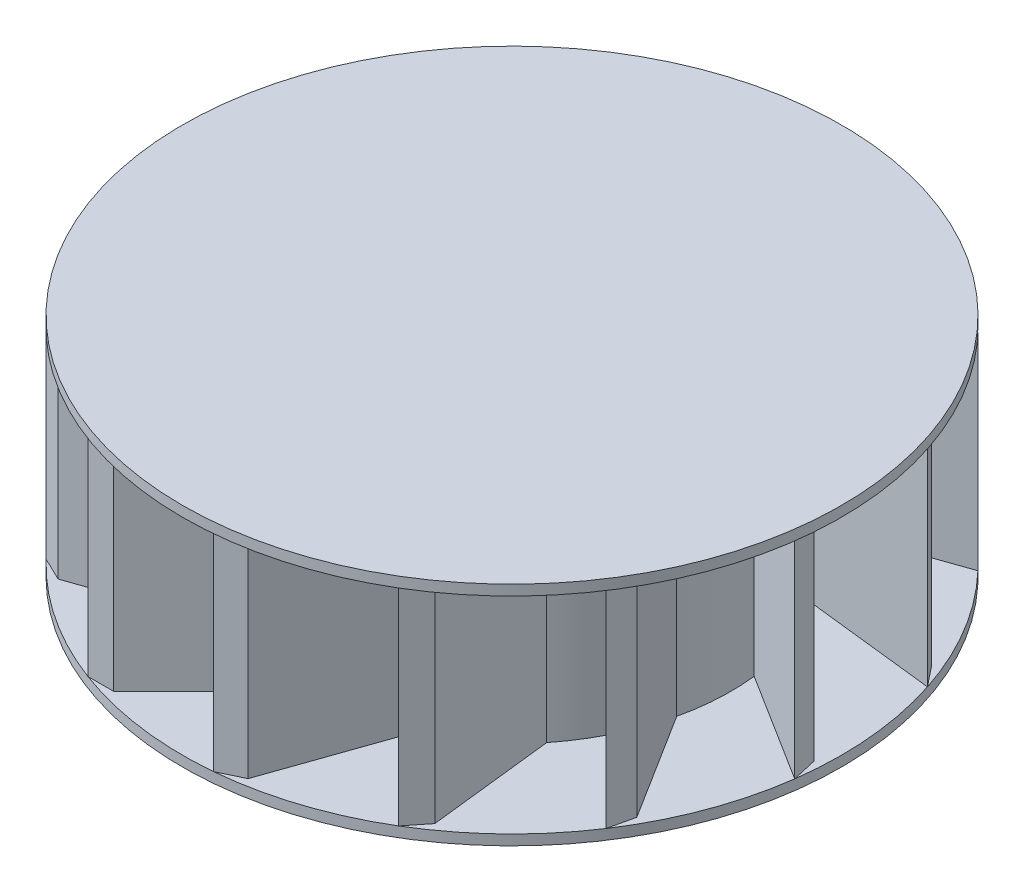
SolidWorks part; units mm, degrees
ref_plane "Front Plane" through (0, 0, 0) normal (0, 0, 1) x (1, 0, 0)
ref_plane "Top Plane" through (0, 0, 0) normal (0, 1, 0) x (1, 0, 0)
ref_plane "Right Plane" through (0, 0, 0) normal (1, 0, 0) x (0, 0, -1)
sketch "Sketch1" plane through (0, 0, 0) normal (0, 1, 0) x (1, 0, 0)
  circle A0 centre (0, 0) radius 42.5
  circle A1 centre (0, 0) radius 3.75
  dimension "D4" = 7.5
  dimension "6.5" = 85
extrude "Boss-Extrude1" add sketch "Sketch1" along normal blind 40
sketch "Sketch2" plane through (0, 0, 0) normal (0, -1, 0) x (1, 0, 0)
  line L0 (0, -42.5) -> (17.413, -59.913)
  line L1 (17.413, -59.913) -> (22.413, -59.913)
  line L2 (22.413, -59.913) -> (4.7354, -42.2354)
  line L4 (0, -42.5) -> (17.0282, -42.5) construction
  line L5 (-18.4401, -38.2912) -> (-10.3067, -61.535)
  line L6 (-5.8018, -63.7044) -> (-14.0588, -40.1074)
  line L7 (-10.3067, -61.535) -> (-5.8018, -63.7044)
  line L8 (-33.2278, -26.4983) -> (-35.985, -50.9692)
  line L9 (-32.8676, -54.8784) -> (-30.0685, -30.0356)
  line L10 (-35.985, -50.9692) -> (-32.8676, -54.8784)
  line L11 (-41.4344, -9.4571) -> (-54.5361, -30.3084)
  line L12 (-53.4235, -35.183) -> (-40.1227, -14.0149)
  line L13 (-54.5361, -30.3084) -> (-53.4235, -35.183)
  line L14 (-41.4344, 9.4571) -> (-62.2857, -3.6446)
  line L15 (-63.3983, -8.5192) -> (-42.2302, 4.7816)
  line L16 (-62.2857, -3.6446) -> (-63.3983, -8.5192)
  line L17 (-33.2278, 26.4983) -> (-57.6987, 23.7411)
  line L18 (-60.8162, 19.8319) -> (-35.9734, 22.6311)
  line L19 (-57.6987, 23.7411) -> (-60.8162, 19.8319)
  line L20 (-18.4401, 38.2912) -> (-41.6839, 46.4245)
  line L21 (-46.1887, 44.2551) -> (-22.5917, 35.9982)
  line L22 (-41.6839, 46.4245) -> (-46.1887, 44.2551)
  line L23 (0, 42.5) -> (-17.413, 59.913)
  line L24 (-22.413, 59.913) -> (-4.7354, 42.2354)
  line L25 (-17.413, 59.913) -> (-22.413, 59.913)
  line L26 (18.4401, 38.2912) -> (10.3067, 61.535)
  line L27 (5.8018, 63.7044) -> (14.0588, 40.1074)
  line L28 (10.3067, 61.535) -> (5.8018, 63.7044)
  line L29 (33.2278, 26.4983) -> (35.985, 50.9692)
  line L30 (32.8676, 54.8784) -> (30.0685, 30.0356)
  line L31 (35.985, 50.9692) -> (32.8676, 54.8784)
  line L32 (41.4344, 9.4571) -> (54.5361, 30.3084)
  line L33 (53.4235, 35.183) -> (40.1227, 14.0149)
  line L34 (54.5361, 30.3084) -> (53.4235, 35.183)
  line L35 (41.4344, -9.4571) -> (62.2857, 3.6446)
  line L36 (63.3983, 8.5192) -> (42.2302, -4.7816)
  line L37 (62.2857, 3.6446) -> (63.3983, 8.5192)
  line L38 (33.2278, -26.4983) -> (57.6987, -23.7411)
  line L39 (60.8162, -19.8319) -> (35.9734, -22.6311)
  line L40 (57.6987, -23.7411) -> (60.8162, -19.8319)
  line L41 (18.4401, -38.2912) -> (41.6839, -46.4245)
  line L42 (46.1887, -44.2551) -> (22.5917, -35.9982)
  line L43 (41.6839, -46.4245) -> (46.1887, -44.2551)
  circle A0 centre (0, 0) radius 42.5 construction
  arc A1 (0, -42.5) -> (4.7354, -42.2354) centre (0, 0) ccw
  arc A2 (-18.4401, -38.2912) -> (-14.0588, -40.1074) centre (0, 0) ccw
  arc A3 (-33.2278, -26.4983) -> (-30.0685, -30.0356) centre (0, 0) ccw
  arc A4 (-41.4344, -9.4571) -> (-40.1227, -14.0149) centre (0, 0) ccw
  arc A5 (-41.4344, 9.4571) -> (-42.2302, 4.7816) centre (0, 0) ccw
  arc A6 (-33.2278, 26.4983) -> (-35.9734, 22.6311) centre (0, 0) ccw
  arc A7 (-18.4401, 38.2912) -> (-22.5917, 35.9982) centre (0, 0) ccw
  arc A8 (0, 42.5) -> (-4.7354, 42.2354) centre (0, 0) ccw
  arc A9 (18.4401, 38.2912) -> (14.0588, 40.1074) centre (0, 0) ccw
  arc A10 (33.2278, 26.4983) -> (30.0685, 30.0356) centre (0, 0) ccw
  arc A11 (41.4344, 9.4571) -> (40.1227, 14.0149) centre (0, 0) ccw
  arc A12 (41.4344, -9.4571) -> (42.2302, -4.7816) centre (0, 0) ccw
  arc A13 (33.2278, -26.4983) -> (35.9734, -22.6311) centre (0, 0) ccw
  arc A14 (18.4401, -38.2912) -> (22.5917, -35.9982) centre (0, 0) ccw
  point P62 (0, 0)
  dimension "D1" = 45
  dimension "D2" = 5
  dimension "D3" = 25
  dimension "D4" = 14
extrude "Boss-Extrude2" add sketch "Sketch2" against normal blind 40
sketch "Sketch3" plane through (0, 0, 0) normal (0, -1, 0) x (1, 0, 0)
  circle A0 centre (0, 0) radius 63.9681
extrude "Boss-Extrude3" add sketch "Sketch3" along normal blind 2 contours A0
sketch "Sketch4" plane through (0, 40, 0) normal (0, 1, 0) x (1, 0, 0)
  circle A0 centre (0, 0) radius 63.9681
extrude "Boss-Extrude4" add sketch "Sketch4" along normal blind 2
sketch "Sketch6" plane through (0, -2, 0) normal (0, -1, 0) x (1, 0, 0)
  circle A0 centre (0, 0) radius 3.75
  dimension "D1" = 7.5
extrude "Cut-Extrude1" cut sketch "Sketch6" against normal blind 79
